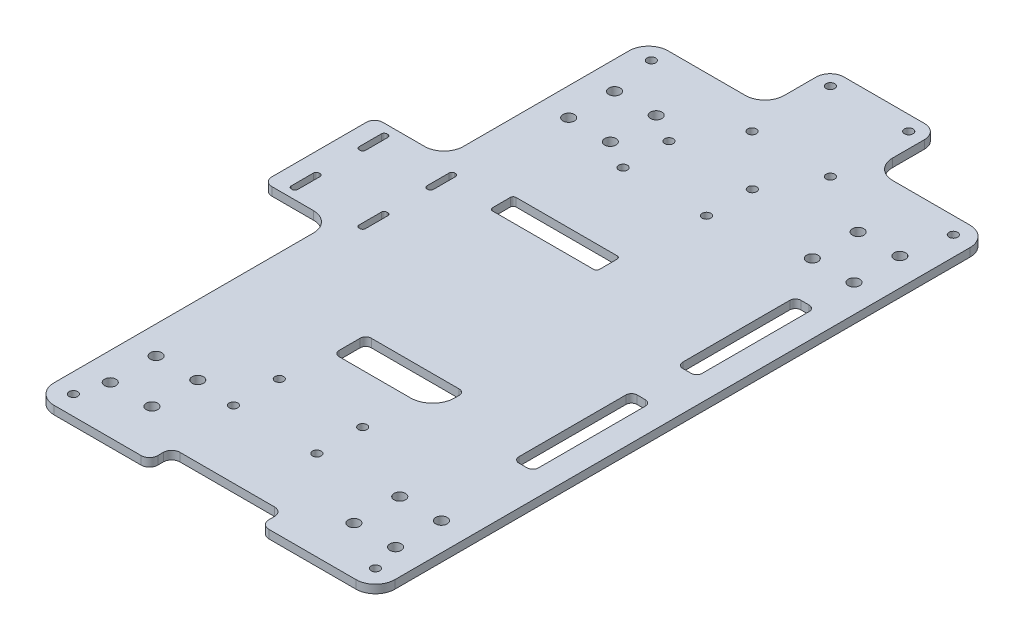
SolidWorks part; units mm, degrees
ref_plane "Front Plane" through (0, 0, 0) normal (0, 0, 1) x (1, 0, 0)
ref_plane "Top Plane" through (0, 0, 0) normal (0, 1, 0) x (1, 0, 0)
ref_plane "Right Plane" through (0, 0, 0) normal (1, 0, 0) x (0, 0, -1)
sketch "Sketch1" plane through (0, 0, 0) normal (0, 1, 0) x (1, 0, 0)
  line L0 (0, 132.1036) -> (0, -142.6838) construction
  line L1 (-61.35, 100) -> (61.35, 100)
  line L2 (-61.35, 100) -> (-61.35, -100)
  line L3 (-61.35, -100) -> (61.35, -100)
  line L4 (61.35, 100) -> (61.35, -100)
  line L5 (-61.35, 100) -> (61.35, -100) construction
  line L6 (-61.35, -100) -> (61.35, 100) construction
  line L7 (0, -55) -> (0, 55) construction
  line L8 (-189.9448, 0) -> (195.6261, 0) construction
  line L9 (18.5, 87.6829) -> (18.5, -193.4849) construction
  line L10 (-39.5, 87.6829) -> (-39.5, -193.4849) construction
  point P0 (0, 0)
  dimension "D1" = 122.7
  dimension "D2" = 200
extrude "Boss-Extrude1" add sketch "Sketch1" along normal blind 3
sketch "Sketch2" plane through (0, 3, 0) normal (0, 1, 0) x (1, 0, 0)
  line L0 (-162.8834, 0) -> (150.0475, 0) construction
  line L1 (0, 129.9084) -> (0, -141.4164) construction
  line L3 (-18.1521, -29.9956) -> (13.5, -29.9956)
  line L4 (-20.1521, -31.9956) -> (-20.1521, -39.5537)
  line L5 (-18.1521, -41.5537) -> (7.5, -41.5537)
  line L6 (15.5, -31.9956) -> (15.5, -33.5537)
  line L7 (-36.0134, 39.9424) -> (0.4565, 39.9424)
  line L8 (-37.0134, 38.9424) -> (-37.0134, 32.4822)
  line L9 (-36.0134, 31.4822) -> (0.4565, 31.4822)
  line L10 (1.4565, 38.9424) -> (1.4565, 32.4822)
  arc A0 (15.5, -31.9956) -> (13.5, -29.9956) centre (13.5, -31.9956) ccw
  arc A1 (-18.1521, -41.5537) -> (-20.1521, -39.5537) centre (-18.1521, -39.5537) cw
  arc A2 (-20.1521, -31.9956) -> (-18.1521, -29.9956) centre (-18.1521, -31.9956) cw
  arc A3 (7.5, -41.5537) -> (15.5, -33.5537) centre (7.5, -33.5537) ccw
  arc A4 (0.4565, 39.9424) -> (1.4565, 38.9424) centre (0.4565, 38.9424) cw
  arc A5 (0.4565, 31.4822) -> (1.4565, 32.4822) centre (0.4565, 32.4822) ccw
  arc A6 (-36.0134, 31.4822) -> (-37.0134, 32.4822) centre (-36.0134, 32.4822) cw
  arc A7 (-37.0134, 38.9424) -> (-36.0134, 39.9424) centre (-36.0134, 38.9424) cw
  circle A8 centre (20.5, -44) radius 1.05 construction
  dimension "D1" = 2
  dimension "D2" = 8
  dimension "D3" = 1
  dimension "D5" = 5
extrude "Cut-Extrude1" cut sketch "Sketch2" against normal up to surface (3 mm away) up to face at (0, 0, 0)
sketch "Sketch3" plane through (0, 3, 0) normal (0, 1, 0) x (1, 0, 0)
  line L0 (61.35, -100) -> (61.35, 100) construction
  line L1 (0, 125.5002) -> (0, -134.5016) construction
  line L2 (-137.7639, 0) -> (136.9662, 0) construction
  line L3 (-1.65, 0) -> (1.65, 0) construction
  line L4 (61.35, 100) -> (-61.35, 100) construction
  line L5 (51.35, 90.75) -> (51.35, 74.25) construction
  line L6 (51.35, 82.5) -> (90.3323, 82.5) construction
  line L7 (0, -1.65) -> (0, 1.65) construction
  line L8 (-51.35, 90.75) -> (-51.35, 74.25) construction
  line L9 (-51.35, 82.5) -> (-90.3323, 82.5) construction
  line L10 (51.35, -90.75) -> (51.35, -74.25) construction
  line L11 (51.35, -82.5) -> (90.3323, -82.5) construction
  line L12 (-51.35, -90.75) -> (-51.35, -74.25) construction
  line L13 (-51.35, -82.5) -> (-90.3323, -82.5) construction
  circle A0 centre (51.35, 90.75) radius 2.05
  circle A1 centre (36.35, 90.75) radius 2.05
  circle A2 centre (36.35, 74.25) radius 2.05
  circle A3 centre (51.35, 74.25) radius 2.05
  circle A4 centre (-51.35, 74.25) radius 2.05
  circle A5 centre (-36.35, 74.25) radius 2.05
  circle A6 centre (-36.35, 90.75) radius 2.05
  circle A7 centre (-51.35, 90.75) radius 2.05
  circle A8 centre (-51.35, -90.75) radius 2.05
  circle A9 centre (-36.35, -90.75) radius 2.05
  circle A10 centre (-36.35, -74.25) radius 2.05
  circle A11 centre (-51.35, -74.25) radius 2.05
  circle A12 centre (51.35, -74.25) radius 2.05
  circle A13 centre (36.35, -74.25) radius 2.05
  circle A14 centre (36.35, -90.75) radius 2.05
  circle A15 centre (51.35, -90.75) radius 2.05
  dimension "D1" = 4.1
  dimension "D2" = 10
  dimension "D3" = 4.1
  dimension "D4" = 15
  dimension "D6" = 16.5
  dimension "D7" = 9.25
  dimension "D9" = 180.6646
  dimension "D5" = 2
sketch "Sketch4" plane through (0, 3, 0) normal (0, 1, 0) x (1, 0, 0)
  line L0 (-61.35, 100) -> (-61.35, -100) construction
  line L5 (0, 125.5002) -> (0, -134.5016) construction
  line L6 (0, 147.4469) -> (0, 90.5728) construction
  line L7 (20.1578, 117.1) -> (-23.4234, 117.1) construction
  line L12 (61.35, 100) -> (-61.35, 100) construction
  line L13 (-19.5, 100) -> (19.5, 100)
  line L14 (-19.5, 115) -> (-19.5, 136.5)
  line L15 (-19.5, 136.5) -> (19.5, 136.5)
  line L16 (19.5, 115) -> (19.5, 136.5)
  line L17 (34.5, 100) -> (19.5, 100)
  line L18 (-34.5, 100) -> (-19.5, 100)
  line L19 (-61.35, 39.3757) -> (-86.35, 39.3757)
  line L20 (-61.35, 39.3757) -> (-61.35, -0.6243)
  line L21 (-61.35, -0.6243) -> (-86.35, -0.6243)
  line L22 (-86.35, 39.3757) -> (-86.35, -0.6243)
  circle A0 centre (14.1, 103) radius 1.55
  circle A1 centre (-14.1, 103) radius 1.55
  circle A2 centre (14.1, 131.2) radius 1.55
  circle A3 centre (-14.1, 131.2) radius 1.55
  arc A4 (19.5, 115) -> (34.5, 100) centre (34.5, 115) ccw
  arc A5 (-19.5, 115) -> (-34.5, 100) centre (-34.5, 115) cw
  dimension "D4" = 3.1
  dimension "D5" = 15
  dimension "D6" = 25
  dimension "D7" = 28.2
  dimension "D9" = 28.2
  dimension "D1" = 40
  dimension "D2" = 36.5
  dimension "D3" = 19.5
extrude "Boss-Extrude2" add sketch "Sketch4" against normal up to surface (3 mm away) up to face at (-2.9207, 0, 35.18)
extrude "Cut-Extrude2" cut sketch "Sketch3" against normal through all
sketch "Sketch5" plane through (0, 3, 0) normal (0, 1, 0) x (1, 0, 0)
  line L0 (-119.2376, 0) -> (145.54, 0) construction
  line L1 (-66.6947, 34.8534) -> (-66.6947, 2.369) construction
  line L2 (-79.0447, 36.5234) -> (-78.7447, 36.5234)
  line L3 (-80.0447, 35.5234) -> (-80.0447, 27.5234)
  line L4 (-79.0447, 26.5234) -> (-78.7447, 26.5234)
  line L5 (-77.7447, 35.5234) -> (-77.7447, 27.5234)
  line L6 (-80.0447, 36.5234) -> (-77.7447, 26.5234) construction
  line L7 (-80.0447, 26.5234) -> (-77.7447, 36.5234) construction
  line L8 (-82.0133, 19.3234) -> (-45.889, 19.3234) construction
  line L21 (-53.3447, 26.5234) -> (-55.6447, 36.5234) construction
  line L22 (-53.3447, 36.5234) -> (-55.6447, 26.5234) construction
  line L23 (-55.6447, 35.5234) -> (-55.6447, 27.5234)
  line L24 (-54.3447, 26.5234) -> (-54.6447, 26.5234)
  line L25 (-53.3447, 35.5234) -> (-53.3447, 27.5234)
  line L26 (-54.3447, 36.5234) -> (-54.6447, 36.5234)
  line L27 (-53.3447, 2.1234) -> (-55.6447, 12.1234) construction
  line L28 (-53.3447, 12.1234) -> (-55.6447, 2.1234) construction
  line L29 (-80.0447, 12.1234) -> (-77.7447, 2.1234) construction
  line L30 (-80.0447, 2.1234) -> (-77.7447, 12.1234) construction
  line L31 (-54.3447, 2.1234) -> (-54.6447, 2.1234)
  line L32 (-53.3447, 3.1234) -> (-53.3447, 11.1234)
  line L33 (-54.3447, 12.1234) -> (-54.6447, 12.1234)
  line L34 (-55.6447, 3.1234) -> (-55.6447, 11.1234)
  line L35 (-77.7447, 3.1234) -> (-77.7447, 11.1234)
  line L36 (-79.0447, 12.1234) -> (-78.7447, 12.1234)
  line L37 (-80.0447, 3.1234) -> (-80.0447, 11.1234)
  line L38 (-79.0447, 2.1234) -> (-78.7447, 2.1234)
  arc A0 (-78.7447, 36.5234) -> (-77.7447, 35.5234) centre (-78.7447, 35.5234) cw
  arc A1 (-80.0447, 35.5234) -> (-79.0447, 36.5234) centre (-79.0447, 35.5234) cw
  arc A2 (-77.7447, 27.5234) -> (-78.7447, 26.5234) centre (-78.7447, 27.5234) cw
  arc A3 (-80.0447, 27.5234) -> (-79.0447, 26.5234) centre (-79.0447, 27.5234) ccw
  arc A16 (-53.3447, 27.5234) -> (-54.3447, 26.5234) centre (-54.3447, 27.5234) cw
  arc A17 (-55.6447, 27.5234) -> (-54.6447, 26.5234) centre (-54.6447, 27.5234) ccw
  arc A18 (-53.3447, 35.5234) -> (-54.3447, 36.5234) centre (-54.3447, 35.5234) ccw
  arc A19 (-54.6447, 36.5234) -> (-55.6447, 35.5234) centre (-54.6447, 35.5234) ccw
  arc A20 (-54.6447, 2.1234) -> (-55.6447, 3.1234) centre (-54.6447, 3.1234) cw
  arc A21 (-53.3447, 3.1234) -> (-54.3447, 2.1234) centre (-54.3447, 3.1234) cw
  arc A22 (-55.6447, 11.1234) -> (-54.6447, 12.1234) centre (-54.6447, 11.1234) cw
  arc A23 (-53.3447, 11.1234) -> (-54.3447, 12.1234) centre (-54.3447, 11.1234) ccw
  arc A24 (-80.0447, 11.1234) -> (-79.0447, 12.1234) centre (-79.0447, 11.1234) cw
  arc A25 (-77.7447, 11.1234) -> (-78.7447, 12.1234) centre (-78.7447, 11.1234) ccw
  arc A26 (-80.0447, 3.1234) -> (-79.0447, 2.1234) centre (-79.0447, 3.1234) ccw
  arc A27 (-78.7447, 2.1234) -> (-77.7447, 3.1234) centre (-78.7447, 3.1234) ccw
  point P3 (-78.8947, 31.5234)
  point P41 (-54.4947, 31.5234)
  point P74 (-54.4947, 7.1234)
  point P75 (-78.8947, 7.1234)
  dimension "D3" = 1
  dimension "D1" = 10
  dimension "D2" = 2.3
  dimension "D4" = 12.2
  dimension "D5" = 12.2
extrude "Cut-Extrude3" cut sketch "Sketch5" against normal through all
fillet "Fillet1" radius 5 2 edges at (19.5, 1.5, -136.5) (-19.5, 1.5, -136.5)
sketch "Sketch8" plane through (0, 3, 0) normal (0, 1, 0) x (1, 0, 0)
  line L0 (-34.5, 100) -> (-61.35, 100) construction
  line L2 (0, 136.5) -> (0, -128.3587) construction
  line L3 (14.5, 136.5) -> (-14.5, 136.5) construction
  circle A0 centre (-26, 85) radius 1.55
  circle A1 centre (-26, 68.5) radius 1.55
  circle A5 centre (-22, -59.25) radius 1.55
  circle A6 centre (-22, -75.75) radius 1.55
  circle A8 centre (4, 85) radius 1.55
  circle A9 centre (4, 68.5) radius 1.55
  circle A10 centre (8, -59.25) radius 1.55
  circle A11 centre (8, -75.75) radius 1.55
  dimension "D1" = 3.1
  dimension "D3" = 3.1
  dimension "D5" = 26
  dimension "D6" = 3.1
  dimension "D7" = 30
  dimension "D8" = 3.1
  dimension "D9" = 30
  dimension "D10" = 16.5
  dimension "D11" = 15
  dimension "D4" = 16.5
  dimension "D2" = 26
extrude "Cut-Extrude4" cut sketch "Sketch8" against normal through all
sketch "Sketch9" plane through (0, 3, 0) normal (0, 1, 0) x (1, 0, 0)
  line L0 (51.35, 90.75) -> (51.35, 124.0445) construction
  line L1 (61.35, 100) -> (34.5, 100)
  line L2 (61.35, 100) -> (61.35, 113)
  line L3 (61.35, 113) -> (19.6339, 113)
  line L4 (-61.35, 100) -> (-61.35, 113)
  line L5 (-61.35, 100) -> (-61.35, 39.3757) construction
  line L6 (0, 140.8565) -> (0, 90.75) construction
  line L7 (-19.6339, 113) -> (-61.35, 113)
  line L8 (-34.5, 100) -> (-61.35, 100)
  arc A1 (-19.6339, 113) -> (-34.5, 100) centre (-34.5, 115) cw
  arc A2 (-34.5, 100) -> (-19.5, 115) centre (-34.5, 115) ccw construction
  arc A3 (19.6339, 113) -> (34.5, 100) centre (34.5, 115) ccw
  dimension "D3" = 13
  dimension "D4" = 0
extrude "Boss-Extrude3" add sketch "Sketch9" against normal up to surface (3 mm away) up to face at (8, 0, 60.8)
sketch "Sketch10" plane through (0, 3, 0) normal (0, 1, 0) x (1, 0, 0)
  line L0 (36.35, 90.75) -> (51.35, 90.75) construction
  line L1 (61.35, -100) -> (61.35, 113) construction
  line L2 (61.35, 113) -> (19.6339, 113) construction
  line L3 (0, 140.8424) -> (0, 94.8188) construction
  circle A0 centre (54.35, 107) radius 1.55
  circle A1 centre (-54.35, 107) radius 1.55
  dimension "D1" = 3.1
  dimension "D2" = 6
  dimension "D3" = 7
extrude "Cut-Extrude5" cut sketch "Sketch10" against normal through all
sketch "Sketch11" plane through (0, 3, 0) normal (0, 1, 0) x (1, 0, 0)
  line L0 (61.35, -100) -> (61.35, 113) construction
  line L1 (-61.35, -100) -> (-20, -100)
  line L2 (-61.35, -100) -> (-61.35, -108)
  line L3 (-61.35, -108) -> (-20, -108)
  line L4 (61.35, -100) -> (61.35, -108)
  line L5 (0, -113.8841) -> (0, -91.245) construction
  line L6 (-20, -100) -> (-20, -108)
  line L7 (20, -100) -> (20, -108)
  line L8 (20, -100) -> (61.35, -100)
  line L9 (20, -108) -> (61.35, -108)
  dimension "D1" = 0
  dimension "D2" = 8
  dimension "D3" = 20
extrude "Boss-Extrude4" add sketch "Sketch11" against normal up to surface (3 mm away) up to face at (54.35, 0, -105.45)
sketch "Sketch12" plane through (0, 3, 0) normal (0, 1, 0) x (1, 0, 0)
  line L0 (36.35, -90.75) -> (51.35, -90.75) construction
  line L1 (43.85, -90.75) -> (43.85, -110.0195) construction
  line L2 (54.35, 107) -> (54.35, -137.0446) construction
  line L3 (20, -108) -> (61.35, -108) construction
  line L4 (0, -113.7036) -> (0, 29.767) construction
  circle A0 centre (54.35, -101) radius 1.55
  circle A2 centre (-54.35, -101) radius 1.55
  dimension "D1" = 3.1
  dimension "D2" = 7
extrude "Cut-Extrude6" cut sketch "Sketch12" against normal through all
sketch "Sketch13" plane through (0, 3, 0) normal (0, 1, 0) x (1, 0, 0)
  line L0 (61.35, -108) -> (61.35, 113) construction
  line L1 (47.35, 0.1614) -> (50.35, 0.1614)
  line L2 (45.35, -1.8386) -> (45.35, -40.3641)
  line L3 (47.35, -42.3641) -> (50.35, -42.3641)
  line L4 (52.35, -1.8386) -> (52.35, -40.3641)
  line L5 (45.35, 57.1391) -> (45.35, 18.6136)
  line L6 (47.35, 59.1391) -> (50.35, 59.1391)
  line L7 (52.35, 57.1391) -> (52.35, 18.6136)
  line L8 (47.35, 16.6136) -> (50.35, 16.6136)
  arc A0 (47.35, -42.3641) -> (45.35, -40.3641) centre (47.35, -40.3641) cw
  arc A1 (50.35, -42.3641) -> (52.35, -40.3641) centre (50.35, -40.3641) ccw
  arc A2 (52.35, -1.8386) -> (50.35, 0.1614) centre (50.35, -1.8386) ccw
  arc A3 (45.35, -1.8386) -> (47.35, 0.1614) centre (47.35, -1.8386) cw
  arc A4 (45.35, 57.1391) -> (47.35, 59.1391) centre (47.35, 57.1391) cw
  arc A5 (47.35, 16.6136) -> (45.35, 18.6136) centre (47.35, 18.6136) cw
  arc A6 (52.35, 57.1391) -> (50.35, 59.1391) centre (50.35, 57.1391) ccw
  arc A7 (50.35, 16.6136) -> (52.35, 18.6136) centre (50.35, 18.6136) ccw
  point P4 (47.35, 0.1614)
  point P13 (52.35, 0.1614)
  point P16 (45.35, 0.1614)
  dimension "D3" = 2
  dimension "D1" = 9
  dimension "D2" = 7
  dimension "D4" = 2
extrude "Cut-Extrude7" cut sketch "Sketch13" against normal through all
fillet "Fillet2" radius 7 8 edges at (61.35, 1.5, 108) (-61.35, 1.5, 0.6243) (-61.35, 1.5, -39.3757) (-61.35, 1.5, 108) (61.35, 1.5, -113) (-61.35, 1.5, -113) (19.6339, 1.5, -113) (-19.6339, 1.5, -113)
fillet "Fillet3" radius 3 6 edges at (20, 1.5, 100) (20, 1.5, 108) (-20, 1.5, 100) (-20, 1.5, 108) (-86.35, 1.5, 0.6243) (-86.35, 1.5, -39.3757)
